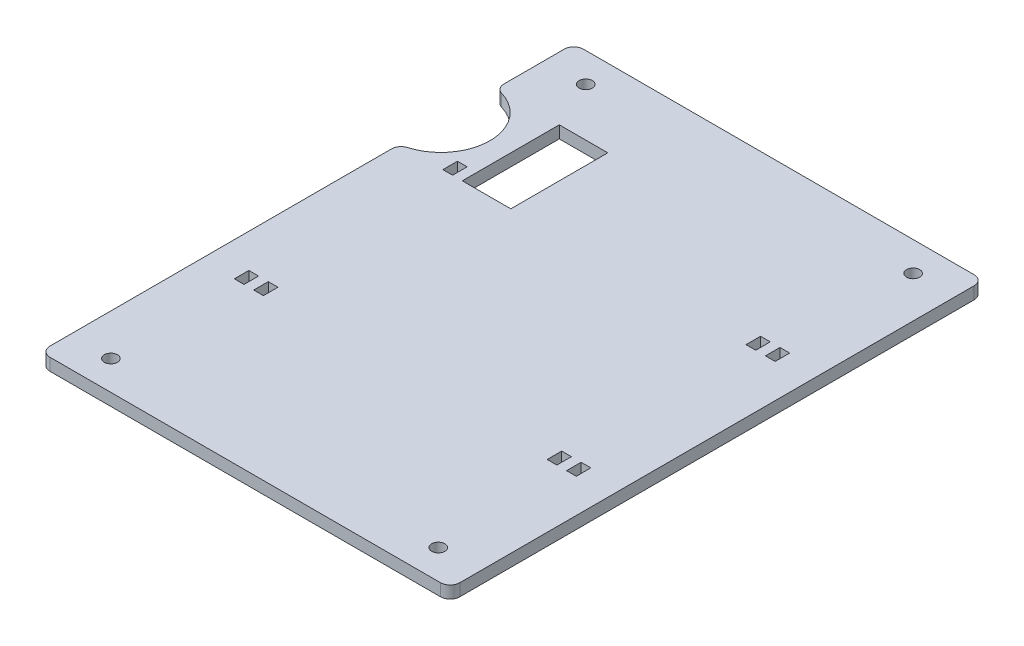
SolidWorks part; units mm, degrees
ref_plane "Front Plane" through (0, 0, 0) normal (0, 0, 1) x (1, 0, 0)
ref_plane "Top Plane" through (0, 0, 0) normal (0, 1, 0) x (1, 0, 0)
ref_plane "Right Plane" through (0, 0, 0) normal (1, 0, 0) x (0, 0, -1)
sketch "Sketch1" plane through (0, 0, 0) normal (0, 1, 0) x (1, 0, 0)
  line L0 (10.795, 132.0165) -> (96.52, 132.0165) construction
  line L1 (0, 139.7) -> (107.315, 139.7)
  line L2 (0, 139.7) -> (0, 0)
  line L3 (0, 0) -> (107.315, 0)
  line L4 (107.315, 139.7) -> (107.315, 0)
  line L5 (10.795, 7.6835) -> (96.52, 7.6835) construction
  line L6 (53.6575, 139.7) -> (53.6575, 132.0165) construction
  line L7 (0, 69.85) -> (107.315, 69.85) construction
  line L8 (53.6575, 7.6835) -> (53.6575, 0) construction
  circle A0 centre (10.795, 132.0165) radius 1.7272
  circle A1 centre (96.52, 132.0165) radius 1.7272
  circle A2 centre (96.52, 7.6835) radius 1.7272
  circle A3 centre (10.795, 7.6835) radius 1.7272
  dimension "D4" = 3.4544
  dimension "D1" = 107.315
  dimension "D2" = 139.7
  dimension "D3" = 85.725
  dimension "D5" = 7.6835
extrude "Boss-Extrude1" add sketch "Sketch1" along normal blind 3.2004
sketch "Sketch2" plane through (0, 3.2004, 0) normal (0, 1, 0) x (1, 0, 0)
  line L0 (0, 139.7) -> (0, 0) construction
  line L2 (0, 119.38) -> (0, 93.98)
  line L3 (107.315, 139.7) -> (0, 139.7) construction
  line L4 (22.86, 106.68) -> (0, 106.68) construction
  line L5 (29.21, 119.38) -> (16.51, 119.38)
  line L6 (29.21, 119.38) -> (29.21, 93.98)
  line L7 (29.21, 93.98) -> (16.51, 93.98)
  line L8 (16.51, 119.38) -> (16.51, 93.98)
  line L9 (22.86, 119.38) -> (22.86, 93.98) construction
  arc A0 (0, 119.38) -> (0, 93.98) centre (-1.7889, 106.68) cw
  point P0 (0, 106.68)
  point P16 (0, 0)
  dimension "D3" = 12.8254
  dimension "D1" = 25.4
  dimension "D2" = 33.02
  dimension "D4" = 22.86
  dimension "D5" = 12.7
  dimension "D6" = 25.4
extrude "Cut-Extrude1" cut sketch "Sketch2" against normal up to surface (3.2004 mm away) up to face at (53.6575, 0, -69.85)
fillet "Fillet1" radius 2.54 6 edges at (0, 1.6002, -93.98) (0, 1.6002, -119.38) (107.315, 1.6002, -139.7) (107.315, 1.6002, 0) (0, 1.6002, 0) (0, 1.6002, -139.7)
sketch "Sketch3" plane through (0, 3.2004, 0) normal (0, 1, 0) x (1, 0, 0)
  line L0 (92.075, 43.815) -> (97.155, 43.815) construction
  line L5 (94.615, 95.885) -> (94.615, 43.815) construction
  line L7 (12.7, 43.815) -> (12.7, 95.885) construction
  line L8 (53.6575, 139.7) -> (53.6575, 0) construction
  line L9 (12.7, 69.85) -> (94.615, 69.85) construction
  line L10 (97.155, 95.885) -> (92.075, 95.885) construction
  line L11 (92.075, 41.91) -> (92.075, 45.72) construction
  line L12 (0, 0) -> (107.315, 0) construction
  line L13 (0, 139.7) -> (107.315, 139.7) construction
  line L29 (90.805, 41.91) -> (90.805, 45.72)
  line L34 (13.97, 95.885) -> (11.43, 95.885) construction
  line L35 (13.97, 97.79) -> (11.43, 97.79)
  line L36 (13.97, 97.79) -> (13.97, 93.98)
  line L37 (13.97, 93.98) -> (11.43, 93.98)
  line L38 (11.43, 97.79) -> (11.43, 93.98)
  line L39 (90.805, 41.91) -> (93.345, 41.91)
  line L44 (16.51, 93.98) -> (29.21, 93.98) construction
  line L45 (16.51, 119.38) -> (16.51, 93.98) construction
  line L46 (93.345, 41.91) -> (93.345, 45.72)
  line L47 (90.805, 45.72) -> (93.345, 45.72)
  line L48 (97.155, 41.91) -> (97.155, 45.72) construction
  line L49 (95.885, 41.91) -> (95.885, 45.72)
  line L50 (95.885, 41.91) -> (98.425, 41.91)
  line L51 (98.425, 41.91) -> (98.425, 45.72)
  line L52 (95.885, 45.72) -> (98.425, 45.72)
  line L53 (97.155, 93.98) -> (97.155, 97.79) construction
  line L54 (98.425, 93.98) -> (98.425, 97.79)
  line L55 (98.425, 93.98) -> (95.885, 93.98)
  line L56 (95.885, 93.98) -> (95.885, 97.79)
  line L57 (98.425, 97.79) -> (95.885, 97.79)
  line L58 (92.075, 93.98) -> (92.075, 97.79) construction
  line L59 (90.805, 93.98) -> (90.805, 97.79)
  line L60 (90.805, 93.98) -> (93.345, 93.98)
  line L61 (93.345, 93.98) -> (93.345, 97.79)
  line L62 (90.805, 97.79) -> (93.345, 97.79)
  line L63 (10.16, 43.815) -> (15.24, 43.815) construction
  line L64 (10.16, 41.91) -> (10.16, 45.72) construction
  line L65 (8.89, 41.91) -> (8.89, 45.72)
  line L66 (8.89, 41.91) -> (11.43, 41.91)
  line L67 (11.43, 41.91) -> (11.43, 45.72)
  line L68 (8.89, 45.72) -> (11.43, 45.72)
  line L69 (15.24, 41.91) -> (15.24, 45.72) construction
  line L70 (13.97, 41.91) -> (13.97, 45.72)
  line L71 (13.97, 41.91) -> (16.51, 41.91)
  line L72 (16.51, 41.91) -> (16.51, 45.72)
  line L73 (13.97, 45.72) -> (16.51, 45.72)
  point P0 (11.7126, 69.85)
  point P18 (53.6575, 69.85)
  point P32 (9.6742, 17.218)
  point P33 (9.6742, 17.218)
  point P34 (9.6742, 17.218)
  dimension "D3" = 2.54
  dimension "D1" = 3.81
  dimension "D2" = 2.54
  dimension "D4" = 5.08
extrude "Cut-Extrude2" cut sketch "Sketch3" against normal up to surface (3.2004 mm away) up to face at (22.86, 0, -106.68)
